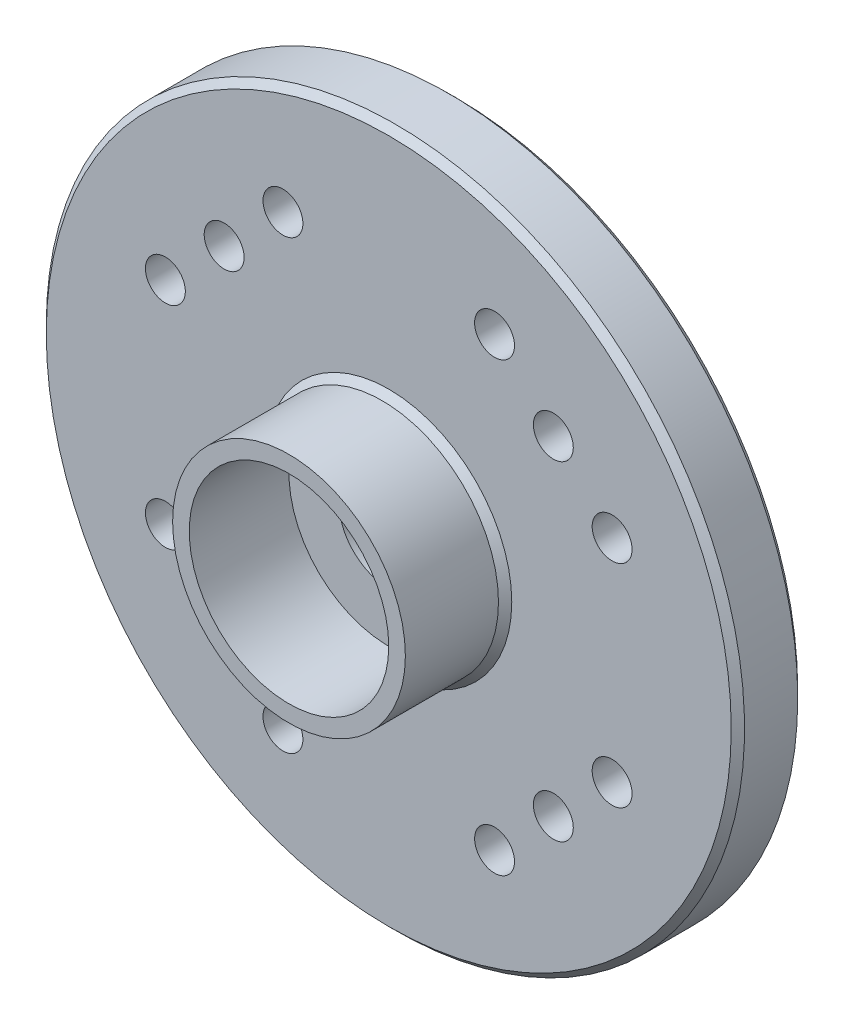
SolidWorks part; units mm, degrees
ref_plane "前视基准面" through (0, 0, 0) normal (0, 0, 1) x (1, 0, 0)
ref_plane "上视基准面" through (0, 0, 0) normal (0, 1, 0) x (1, 0, 0)
ref_plane "右视基准面" through (0, 0, 0) normal (1, 0, 0) x (0, 0, -1)
sketch "草图1" plane through (0, 0, 0) normal (0, 0, 1) x (1, 0, 0)
  circle A0 centre (0, 0) radius 1.5
  circle A1 centre (0, 0) radius 10.5
  dimension "D1" = 21
  dimension "D2" = 3
extrude "凸台-拉伸1" add sketch "草图1" along normal blind 2
sketch "草图2" plane through (0, 0, 2) normal (0, 0, 1) x (1, 0, 0)
  circle A0 centre (0, 0) radius 3.5
  circle A1 centre (0, 0) radius 1.5 construction
  circle A2 centre (0, 0) radius 3
  dimension "D1" = 7
  dimension "D2" = 6
extrude "凸台-拉伸2" add sketch "草图2" along normal blind 3
sketch "草图3" plane through (0, 0, 0) normal (0, 0, -1) x (-1, 0, 0)
  circle A0 centre (0, 0) radius 3
  dimension "D1" = 6
extrude "切除-拉伸1" cut sketch "草图3" against normal blind 1
sketch "草图4" plane through (0, 0, 2) normal (0, 0, 1) x (1, 0, 0)
  line L0 (-4.9497, 4.9497) -> (-3.182, 6.7175) construction
  line L1 (-4.9497, -4.9497) -> (4.9497, -4.9497) construction
  line L2 (-4.9497, -4.9497) -> (-4.9497, 4.9497) construction
  line L3 (-4.9497, 4.9497) -> (4.9497, 4.9497) construction
  line L4 (4.9497, -4.9497) -> (4.9497, 4.9497) construction
  line L5 (-4.9497, -4.9497) -> (4.9497, 4.9497) construction
  line L6 (-4.9497, 4.9497) -> (4.9497, -4.9497) construction
  circle A0 centre (-4.9497, 4.9497) radius 0.6
  circle A1 centre (4.9497, 4.9497) radius 0.6
  circle A2 centre (-4.9497, -4.9497) radius 0.6
  circle A3 centre (4.9497, -4.9497) radius 0.6
  circle A4 centre (-3.182, 6.7175) radius 0.6
  circle A5 centre (-6.7175, 3.182) radius 0.6
  circle A6 centre (6.7175, 3.182) radius 0.6
  circle A7 centre (3.182, 6.7175) radius 0.6
  circle A8 centre (3.182, -6.7175) radius 0.6
  circle A9 centre (6.7175, -3.182) radius 0.6
  circle A10 centre (-6.7175, -3.182) radius 0.6
  circle A11 centre (-3.182, -6.7175) radius 0.6
  point P0 (0, 0)
  dimension "D2" = 1.2
  dimension "D1" = 14
  dimension "D3" = 2.5
  dimension "D4" = 4
extrude "切除-拉伸2" cut sketch "草图4" against normal blind 2
chamfer "倒角1" distance 0.2 angle 45 3 edges at (3.5, 0, 2) (10.5, 0, 0) (10.5, 0, 2)
